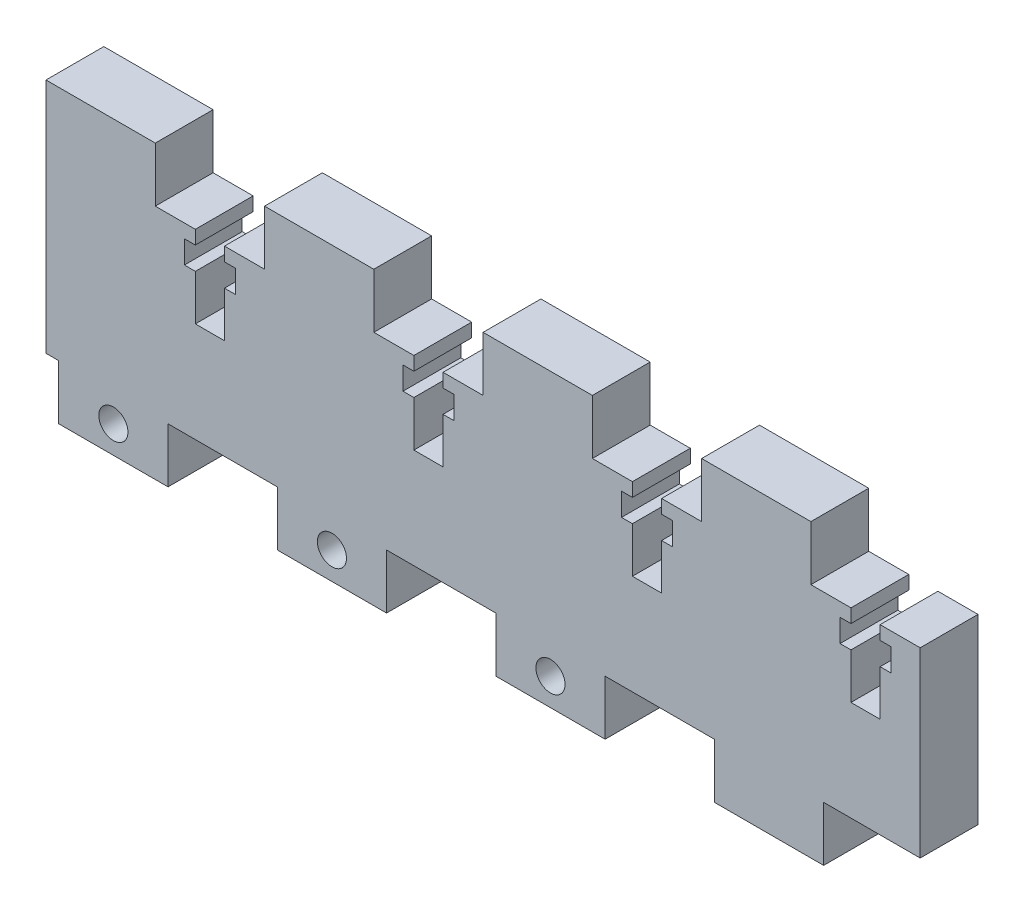
SolidWorks part; units mm, degrees
other "Markup1"
sketch "Sketch5" plane through (-48, -16, 6.35) normal (-0.1716, -0.0555, 0.9836) x (0.9455, 0.2713, 0.1802)
ref_plane "Front Plane" through (0, 0, 0) normal (0, 0, 1) x (1, 0, 0)
ref_plane "Top Plane" through (0, 0, 0) normal (0, 1, 0) x (1, 0, 0)
ref_plane "Right Plane" through (0, 0, 0) normal (1, 0, 0) x (0, 0, -1)
sketch "Sketch1" plane through (0, 0, 0) normal (0, 0, 1) x (1, 0, 0)
  line L1 (-48, 10) -> (48, 10)
  line L2 (-48, 10) -> (-48, -10)
  line L3 (-48, -10) -> (48, -10)
  line L4 (48, 10) -> (48, -10)
  line L5 (-48, 10) -> (48, -10) construction
  line L6 (-48, -10) -> (48, 10) construction
  point P0 (0, 0)
  dimension "D1" = 96
  dimension "D2" = 20
extrude "Boss-Extrude1" add sketch "Sketch1" along normal blind 6.35
sketch "Sketch2" plane through (0, 0, 6.35) normal (0, 0, 1) x (1, 0, 0)
  line L1 (-48, 10) -> (-36, 10)
  line L2 (-48, 10) -> (-48, 16)
  line L3 (-48, 16) -> (-36, 16)
  line L4 (-36, 10) -> (-36, 16)
  dimension "D1" = 12
  dimension "D2" = 6
extrude "Boss-Extrude2" add sketch "Sketch2" against normal up to surface (6.35 mm away) up to face at (0, 0, 0)
pattern_linear "LPattern2" count 4 spacing 24 along (1, 0, 0) of "Boss-Extrude2"
sketch "Sketch3" plane through (0, 0, 6.35) normal (0, 0, 1) x (1, 0, 0)
  line L0 (-30, 10) -> (-30, 1) construction
  line L1 (-24, 10) -> (-36, 10) construction
  line L2 (-31.6, 10) -> (-31.6, 8.5)
  line L3 (-28.4, 10) -> (-28.4, 8.5)
  line L4 (-31.6, 8.5) -> (-32.8, 8.5)
  line L5 (-28.4, 8.5) -> (-27.2, 8.5)
  line L6 (-32.8, 8.5) -> (-32.8, 6)
  line L7 (-27.2, 8.5) -> (-27.2, 6)
  line L8 (-32.8, 6) -> (-31.6, 6)
  line L9 (-27.2, 6) -> (-28.4, 6)
  line L10 (-31.6, 6) -> (-31.6, 1)
  line L11 (-28.4, 6) -> (-28.4, 1)
  line L12 (-31.6, 1) -> (-28.4, 1)
  line L13 (-28.4, 10) -> (-31.6, 10)
  line L14 (-7.6, 10) -> (-7.6, 8.5)
  line L15 (-4.4, 10) -> (-4.4, 8.5)
  line L16 (-7.6, 8.5) -> (-8.8, 8.5)
  line L17 (-4.4, 8.5) -> (-3.2, 8.5)
  line L18 (-8.8, 8.5) -> (-8.8, 6)
  line L19 (-3.2, 8.5) -> (-3.2, 6)
  line L20 (-8.8, 6) -> (-7.6, 6)
  line L21 (-3.2, 6) -> (-4.4, 6)
  line L22 (-7.6, 6) -> (-7.6, 1)
  line L23 (-4.4, 6) -> (-4.4, 1)
  line L24 (-7.6, 1) -> (-4.4, 1)
  line L25 (-4.4, 10) -> (-7.6, 10)
  line L26 (-6, 10) -> (-6, 1) construction
  line L27 (16.4, 10) -> (16.4, 8.5)
  line L28 (19.6, 10) -> (19.6, 8.5)
  line L29 (16.4, 8.5) -> (15.2, 8.5)
  line L30 (19.6, 8.5) -> (20.8, 8.5)
  line L31 (15.2, 8.5) -> (15.2, 6)
  line L32 (20.8, 8.5) -> (20.8, 6)
  line L33 (15.2, 6) -> (16.4, 6)
  line L34 (20.8, 6) -> (19.6, 6)
  line L35 (16.4, 6) -> (16.4, 1)
  line L36 (19.6, 6) -> (19.6, 1)
  line L37 (16.4, 1) -> (19.6, 1)
  line L38 (19.6, 10) -> (16.4, 10)
  line L39 (18, 10) -> (18, 1) construction
  line L40 (40.4, 10) -> (40.4, 8.5)
  line L41 (43.6, 10) -> (43.6, 8.5)
  line L42 (40.4, 8.5) -> (39.2, 8.5)
  line L43 (43.6, 8.5) -> (44.8, 8.5)
  line L44 (39.2, 8.5) -> (39.2, 6)
  line L45 (44.8, 8.5) -> (44.8, 6)
  line L46 (39.2, 6) -> (40.4, 6)
  line L47 (44.8, 6) -> (43.6, 6)
  line L48 (40.4, 6) -> (40.4, 1)
  line L49 (43.6, 6) -> (43.6, 1)
  line L50 (40.4, 1) -> (43.6, 1)
  line L51 (43.6, 10) -> (40.4, 10)
  line L52 (42, 10) -> (42, 1) construction
  line L53 (-30, 1) -> (-6, 1) construction
  point P16 (-31.6, 9.25)
  point P17 (-30, 1)
  point P33 (-6, 1)
  point P48 (18, 1)
  point P63 (42, 1)
  dimension "D1" = 1.5
  dimension "D2" = 2.5
  dimension "D3" = 9
  dimension "D4" = 1.6
  dimension "D5" = 2.8
  dimension "D7" = 24
  dimension "D6" = 4
extrude "Cut-Extrude1" cut sketch "Sketch3" against normal through all
sketch "Sketch6" plane through (0, 0, 0) normal (0, 0, 1) x (1, 0, 0)
  line L0 (-48, -10) -> (48, -10) construction
  line L1 (-46.6, -10) -> (-34.6, -10)
  line L2 (-46.6, -10) -> (-46.6, -16)
  line L3 (-46.6, -16) -> (-34.6, -16)
  line L4 (-34.6, -10) -> (-34.6, -16)
  line L5 (-48, 16) -> (-48, -10) construction
  dimension "D1" = 1.4
  dimension "D2" = 6
  dimension "D3" = 12
extrude "Boss-Extrude3" add sketch "Sketch6" along normal up to surface (6.35 mm away) up to face at (4.3636, 7.697, 6.35)
pattern_linear "LPattern3" count 4 spacing 24 along (1, 0, 0) of "Boss-Extrude3"
sketch "Sketch7" plane through (0, 0, 6.35) normal (0, 0, 1) x (1, 0, 0)
  line L2 (-46.6, -16) -> (-34.6, -16) construction
  line L3 (-46.6, -10) -> (-46.6, -16) construction
  circle A0 centre (-40.6, -13) radius 1.6
  point P2 (0, 0)
  point P5 (0, 0)
  dimension "D1" = 3.2
  dimension "D2" = 3
  dimension "D3" = 6
extrude "Cut-Extrude3" cut sketch "Sketch7" against normal through all
pattern_linear "LPattern4" count 3 spacing 24 along (1, 0, 0) of "Cut-Extrude3"
